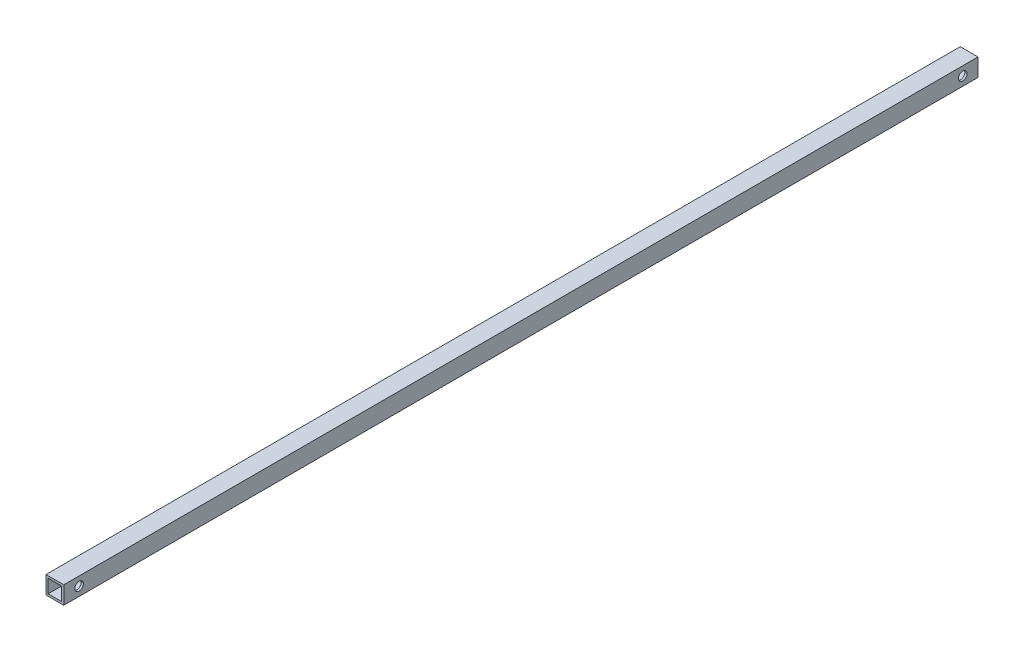
SolidWorks part; units mm, degrees
ref_plane "前视基准面" through (0, 0, 0) normal (0, 0, 1) x (1, 0, 0)
ref_plane "上视基准面" through (0, 0, 0) normal (0, 1, 0) x (1, 0, 0)
ref_plane "右视基准面" through (0, 0, 0) normal (1, 0, 0) x (0, 0, -1)
sketch "草图1" plane through (0, 0, 0) normal (0, 0, 1) x (1, 0, 0)
  line L1 (0, 0) -> (25, 0)
  line L2 (0, 0) -> (0, -25)
  line L3 (0, -25) -> (25, -25)
  line L4 (25, 0) -> (25, -25)
  line L5 (3, -3) -> (22, -3)
  line L6 (3, -3) -> (3, -22)
  line L7 (3, -22) -> (22, -22)
  line L8 (22, -3) -> (22, -22)
  dimension "D1" = 3
  dimension "D2" = 3
  dimension "D3" = 3
  dimension "D4" = 3
  dimension "D5" = 25
  dimension "D6" = 25
extrude "拉伸1" add sketch "草图1" along normal blind 1285.5
hole_wizard "Ø6.0 (6) 直径孔1" positions "草图5" profile "草图4" hole size "Ø6.0" standard "GB"
sketch "草图5" plane through (0, 0, 0) normal (-1, 0, 0) x (0, 0, 1)
  line L0 (1285.5, 0) -> (0, 0) construction
  line L1 (1285.5, 0) -> (1285.5, -25) construction
  point P0 (1264, -12.5)
  dimension "D1" = 12.5
  dimension "D2" = 21.5
sketch "草图4" plane through (0, -12.5, 1264) normal (0, 1, 0) x (0, 0, 1)
  line L0 (0, 0) -> (0, 31.8026)
  line L1 (0, 31.8026) -> (3, 30)
  line L2 (3, 30) -> (3, 0)
  line L5 (3, 0) -> (0, 0)
  line L10 (0, 31.8026) -> (-3, 30) construction
  line L11 (0, -6.35) -> (0, 107.95) construction
  dimension "孔直径" = 6
  dimension "孔深度" = 30
  dimension "导头角度" = 118
sketch "草图6" plane through (25, 0, 0) normal (-1, 0, 0) x (0, 0, 1)
  circle A0 centre (1264, -12.5) radius 6
  dimension "D1" = 12
extrude "切除-拉伸1" cut sketch "草图6" along normal up to surface (3 mm away) up to face at (22, -15.5, 1264)
pattern_linear "阵列(线性)1" count 2 spacing 1242.5 along (0, 0, -1) of "Ø6.0 (6) 直径孔1", "切除-拉伸1"
